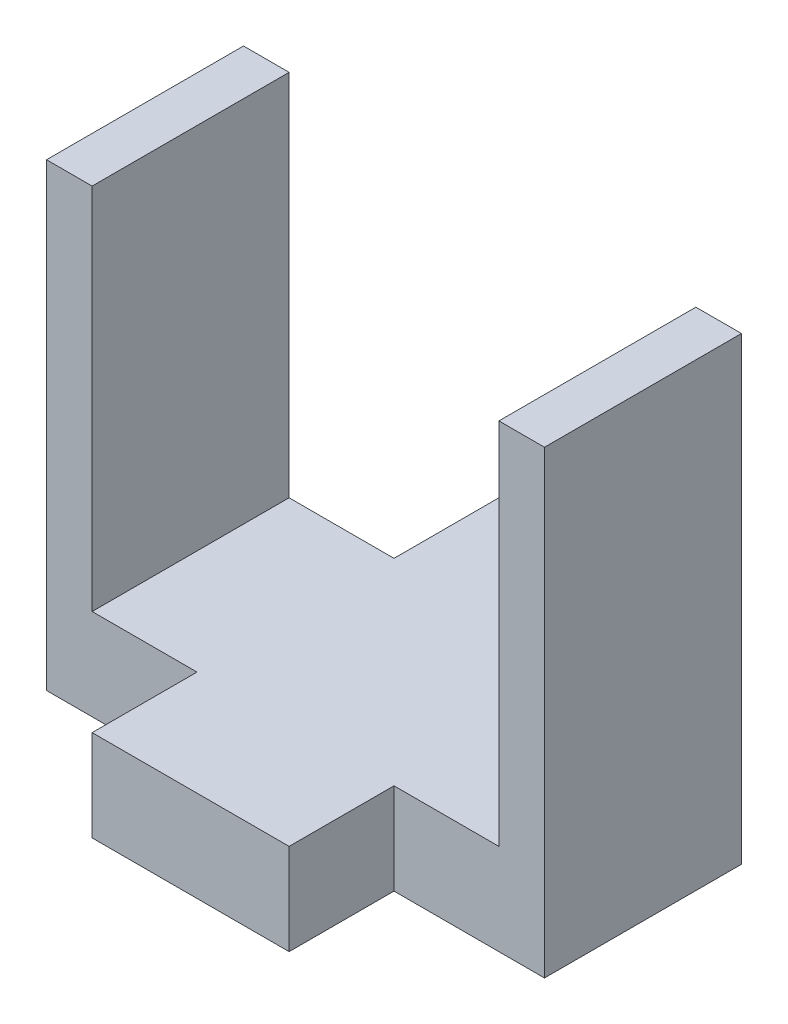
SolidWorks part; units mm, degrees
ref_plane "Plano frontal" through (0, 0, 0) normal (0, 0, 1) x (1, 0, 0)
ref_plane "Plano superior" through (0, 0, 0) normal (0, 1, 0) x (1, 0, 0)
ref_plane "Plano direito" through (0, 0, 0) normal (1, 0, 0) x (0, 0, -1)
sketch "Esboço1" plane through (0, 0, 0) normal (0, 1, 0) x (1, 0, 0)
  line L12 (0, 0) -> (22.3, 0) construction
  line L13 (0, 0) -> (-22.3, 0) construction
  line L14 (0, 0) -> (0, 22.3) construction
  line L15 (0, 0) -> (0, -22.3) construction
  line L18 (-10.8, 22.3) -> (-10.8, 10.8)
  line L19 (-10.8, 10.8) -> (-22.3, 10.8)
  line L28 (-22.3, 10.8) -> (-22.3, -10.8)
  line L29 (-10.8, 22.3) -> (10.8, 22.3)
  line L30 (22.3, 10.8) -> (22.3, -10.8)
  line L31 (10.8, 10.8) -> (22.3, 10.8)
  line L32 (10.8, 22.3) -> (10.8, 10.8)
  line L33 (10.8, -22.3) -> (10.8, -10.8)
  line L34 (10.8, -10.8) -> (22.3, -10.8)
  line L35 (-10.8, -22.3) -> (10.8, -22.3)
  line L36 (-10.8, -10.8) -> (-22.3, -10.8)
  line L37 (-10.8, -22.3) -> (-10.8, -10.8)
  dimension "D1" = 10.8
  dimension "D2" = 10.8
  dimension "D3" = 11.5
  dimension "D4" = 11.5
extrude "Ressalto-extrusão1" add sketch "Esboço1" along normal blind 10
sketch "Esboço2" plane through (0, 0, 0) normal (0, 1, 0) x (1, 0, 0)
  line L0 (0, 22.3) -> (0, -22.3) construction
  line L1 (-10.8, -22.3) -> (10.8, -22.3) construction
  line L2 (10.8, 22.3) -> (-10.8, 22.3) construction
  line L3 (27.3, 10.8) -> (27.3, -10.8)
  line L4 (-22.3, 10.8) -> (-27.3, 10.8)
  line L5 (-22.3, 10.8) -> (-22.3, -10.8)
  line L6 (-22.3, -10.8) -> (-27.3, -10.8)
  line L7 (-27.3, 10.8) -> (-27.3, -10.8)
  line L8 (22.3, -10.8) -> (27.3, -10.8)
  line L9 (22.3, 10.8) -> (22.3, -10.8)
  line L10 (22.3, 10.8) -> (27.3, 10.8)
  dimension "D1" = 21.6
  dimension "D2" = 5
extrude "Ressalto-extrusão2" add sketch "Esboço2" along normal blind 50.4
